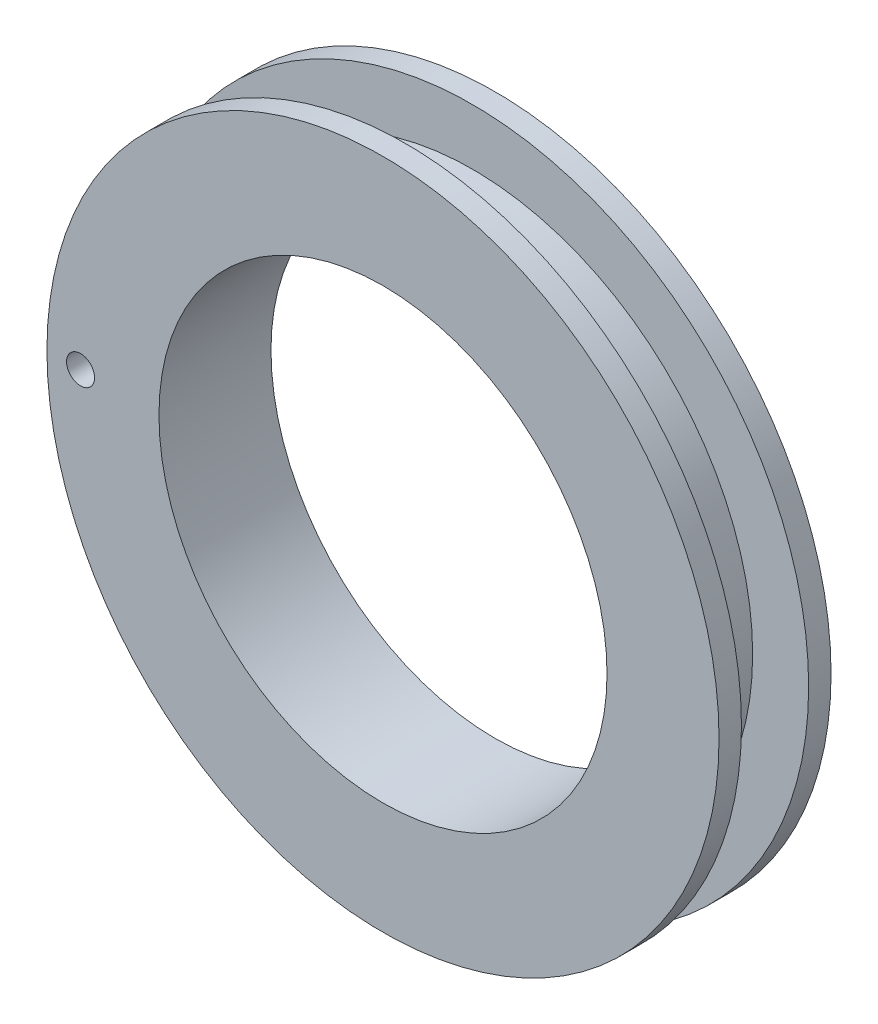
SolidWorks part; units mm, degrees
material "황동"
ref_plane "정면" through (0, 0, 0) normal (0, 0, 1) x (1, 0, 0)
ref_plane "윗면" through (0, 0, 0) normal (0, 1, 0) x (1, 0, 0)
ref_plane "우측면" through (0, 0, 0) normal (1, 0, 0) x (0, 0, -1)
sketch "스케치2" plane through (0, 0, 0) normal (0, 0, 1) x (1, 0, 0)
  circle A0 centre (0, 0) radius 25
  dimension "D1" = 50
extrude "보스-돌출1" add sketch "스케치2" along normal blind 6
sketch "스케치3" plane through (0, 0, 6) normal (0, 0, 1) x (1, 0, 0)
  circle A0 centre (0, 0) radius 30
  dimension "D1" = 60
extrude "보스-돌출2" add sketch "스케치3" along normal blind 2
sketch "스케치4" plane through (0, 0, 0) normal (0, 0, -1) x (-1, 0, 0)
  circle A0 centre (0, 0) radius 30
  dimension "D1" = 60
extrude "보스-돌출4" add sketch "스케치4" along normal blind 2
sketch "스케치5" plane through (0, 0, -2) normal (0, 0, -1) x (-1, 0, 0)
  circle A0 centre (0, 0) radius 20
  dimension "D1" = 40
extrude "컷-돌출1" cut sketch "스케치5" against normal through all both
sketch "스케치6" plane through (0, 0, -2) normal (0, 0, -1) x (-1, 0, 0)
  circle A0 centre (24.9848, 0) radius 2.3292
sketch "스케치7" plane through (0, 0, 8) normal (0, 0, 1) x (1, 0, 0)
  circle A0 centre (-27, 0) radius 1.25
  dimension "D1" = 2.5
  dimension "D2" = 27
extrude "컷-돌출3" cut sketch "스케치7" against normal through all both
